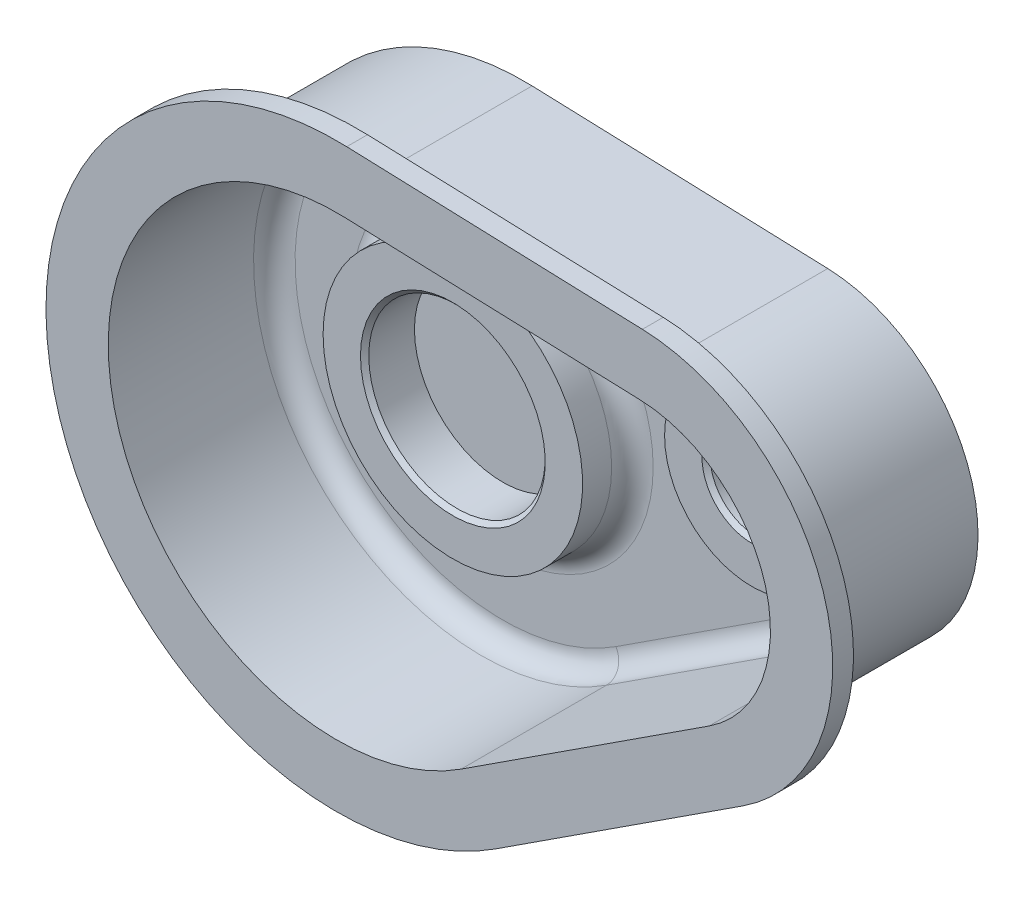
SolidWorks part; units mm, degrees
ref_plane "Front Plane" through (0, 0, 0) normal (0, 0, 1) x (1, 0, 0)
ref_plane "Top Plane" through (0, 0, 0) normal (0, 1, 0) x (1, 0, 0)
ref_plane "Right Plane" through (0, 0, 0) normal (1, 0, 0) x (0, 0, -1)
sketch "Sketch8" plane through (0, 0, 0) normal (0, 0, 1) x (1, 0, 0)
  line L0 (2.0935, 59.9635) -> (73.3084, 57.4772)
  line L1 (92.4502, -11.4331) -> (32.7203, -50.293)
  arc A0 (92.4502, -11.4331) -> (73.3084, 57.4772) centre (72, 20) ccw
  arc A2 (2.0935, 59.9635) -> (32.7203, -50.293) centre (0, 0) ccw
  dimension "D1" = 20
  dimension "D2" = 72
  dimension "D3" = 120
  dimension "D5" = 75
extrude "Boss-Extrude4" add sketch "Sketch8" along normal blind 45
shell "Shell3" thickness 5
sketch "Sketch9" plane through (0, 0, 45) normal (0, 0, 1) x (1, 0, 0)
  line L0 (73.6573, 67.4711) -> (2.4424, 69.9574)
  line L1 (38.1737, -58.6751) -> (97.9035, -19.8153)
  line L2 (32.7203, -50.293) -> (92.4502, -11.4331)
  line L3 (73.3084, 57.4772) -> (2.0935, 59.9635)
  line L4 (32.7203, -50.293) -> (92.4502, -11.4331)
  line L5 (73.3084, 57.4772) -> (2.0935, 59.9635)
  arc A0 (2.4424, 69.9574) -> (38.1737, -58.6751) centre (0, 0) ccw
  arc A1 (97.9035, -19.8153) -> (73.6573, 67.4711) centre (72, 20) ccw
  arc A2 (2.0935, 59.9635) -> (32.7203, -50.293) centre (0, 0) ccw
  arc A3 (92.4502, -11.4331) -> (73.3084, 57.4772) centre (72, 20) ccw
  arc A4 (2.0935, 59.9635) -> (32.7203, -50.293) centre (0, 0) ccw
  arc A5 (92.4502, -11.4331) -> (73.3084, 57.4772) centre (72, 20) ccw
  dimension "D1" = 0
  dimension "D2" = 10
extrude "Boss-Extrude5" add sketch "Sketch9" against normal blind 5
sketch "Sketch10" plane through (0, 0, 5) normal (0, 0, -1) x (-1, 0, 0)
  circle A6 centre (0, 0) radius 21.25
  circle A7 centre (-72, 20) radius 11
  arc A8 (-73.3084, 57.4772) -> (-92.4502, -11.4331) centre (-72, 20) ccw construction
  circle A9 centre (0, 0) radius 31.25
  circle A10 centre (-72, 20) radius 21
  dimension "D1" = 10
  dimension "D2" = 22
  dimension "D3" = 42.5
extrude "Boss-Extrude6" add sketch "Sketch10" against normal blind 12
fillet "Fillet2" radius 5 5 edges at (-52.9935, -14.7204, 5) (37.5265, 53.7234, 5) (103.3143, 28.6984, 5) (31.25, 0, 5) (59.8585, -26.672, 5)
chamfer "Chamfer1" distance 1 angle 45 2 edges at (61, 20, 17) (-21.25, 0, 17)
